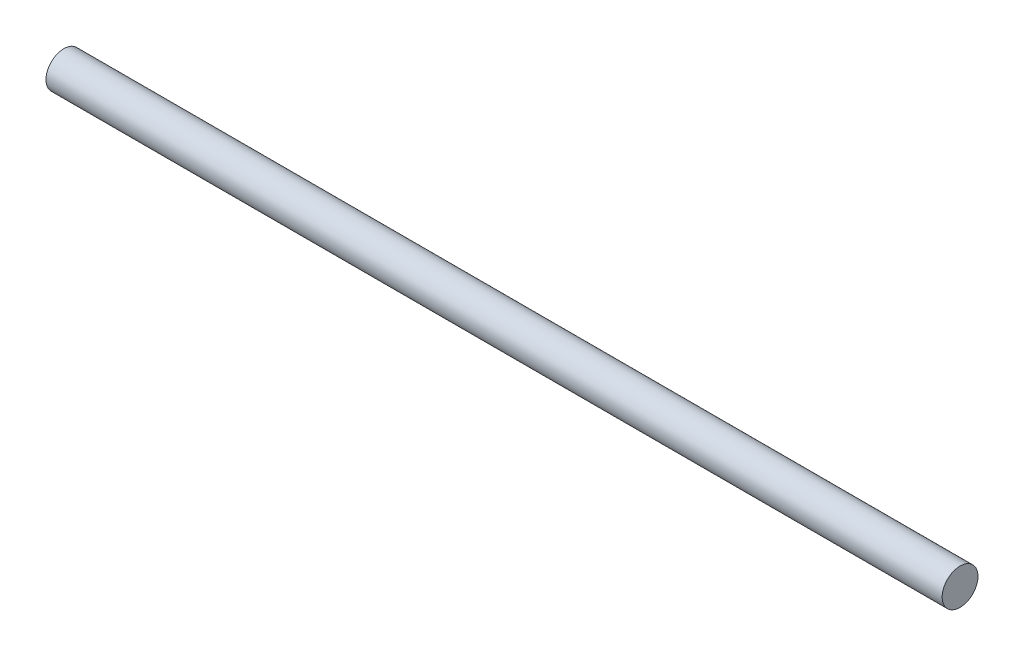
SolidWorks part; units mm, degrees
material "201 Annealed Stainless Steel (SS)"
ref_plane "Front Plane" through (0, 0, 0) normal (0, 0, 1) x (1, 0, 0)
ref_plane "Top Plane" through (0, 0, 0) normal (0, 1, 0) x (1, 0, 0)
ref_plane "Right Plane" through (0, 0, 0) normal (1, 0, 0) x (0, 0, -1)
sketch "Sketch1" plane through (0, 0, 0) normal (1, 0, 0) x (0, 0, -1)
  circle A0 centre (0, 0) radius 4
  dimension "D1" = 8
extrude "Boss-Extrude1" add sketch "Sketch1" along normal blind 200
